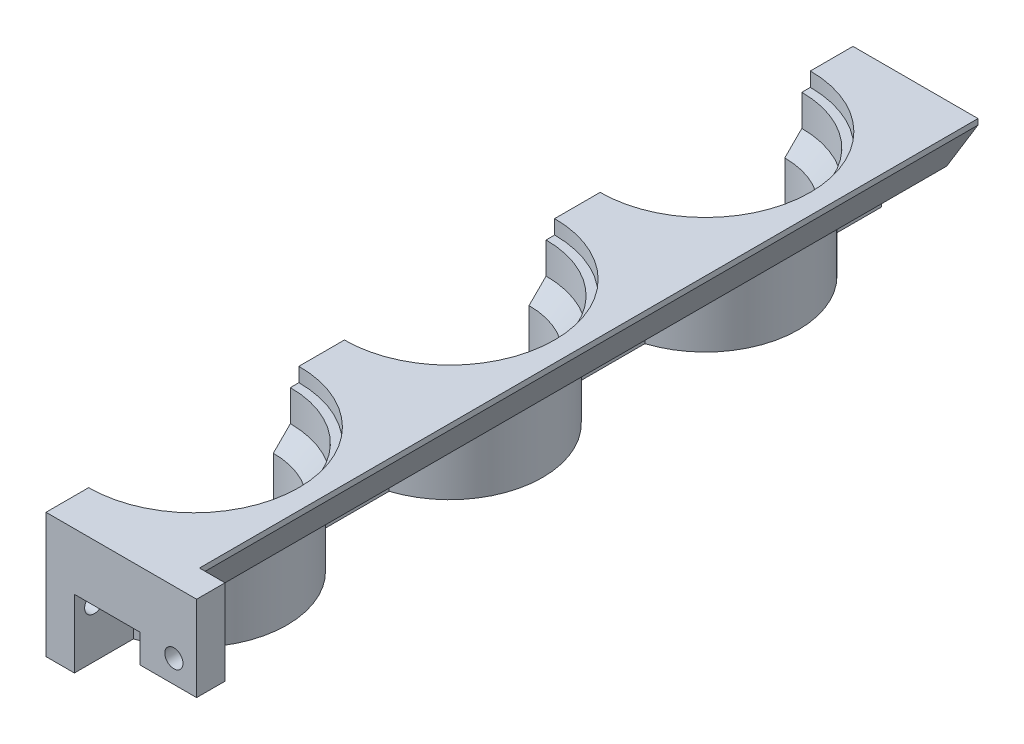
SolidWorks part; units mm, degrees
ref_plane "Płaszczyzna przednia" through (0, 0, 0) normal (0, 0, 1) x (1, 0, 0)
ref_plane "Płaszczyzna górna" through (0, 0, 0) normal (0, 1, 0) x (1, 0, 0)
ref_plane "Płaszczyzna prawa" through (0, 0, 0) normal (1, 0, 0) x (0, 0, -1)
sketch "Sketch1" plane through (0, 0, 0) normal (0, 1, 0) x (1, 0, 0)
  line L0 (0, 65.8555) -> (0, -65.8555) construction
  line L1 (0, -11.4) -> (0, -26)
  line L2 (0, -26) -> (22, -26)
  line L3 (104.3478, 45) -> (-104.3478, 45) construction
  line L4 (22, -26) -> (22, 116)
  line L5 (0, 101.4) -> (0, 116)
  line L6 (0, 116) -> (22, 116)
  line L7 (0, 11.4) -> (0, 33.6)
  line L8 (0, 56.4) -> (0, 78.6)
  arc A6 (0, -11.4) -> (0, 11.4) centre (0, 0) ccw
  arc A7 (0, 33.6) -> (0, 56.4) centre (0, 45) ccw
  arc A8 (0, 78.6) -> (0, 101.4) centre (0, 90) ccw
  point P7 (0, 0)
  point P20 (0, 45)
  point P23 (22, 45)
  dimension "D1" = 71
  dimension "D2" = 11.4
  dimension "D3" = 45
  dimension "D6" = 3
  dimension "D5" = 22
extrude "Boss-Extrude1" add sketch "Sketch1" against normal blind 10
sketch "Sketch3" plane through (0, -10, 0) normal (0, -1, 0) x (1, 0, 0)
  line L23 (0, -116) -> (0, -101.4)
  line L24 (0, -78.6) -> (0, -56.4)
  line L25 (0, -33.6) -> (0, -11.4)
  line L26 (0, 11.4) -> (0, 26)
  line L27 (5, -116) -> (5, -105.6192)
  line L28 (5, -74.3808) -> (5, -60.6192)
  line L29 (5, -29.3808) -> (5, -15.6192)
  line L30 (5, 15.6192) -> (5, 26)
  line L31 (5, -116) -> (5, -105.6192)
  line L32 (5, -74.3808) -> (5, -60.6192)
  line L33 (5, -29.3808) -> (5, -15.6192)
  line L34 (5, 15.6192) -> (5, 26)
  line L35 (0, 26) -> (5, 26)
  line L36 (0, -116) -> (5, -116)
  arc A15 (0, -101.4) -> (0, -78.6) centre (0, -90) ccw
  arc A16 (0, -56.4) -> (0, -33.6) centre (0, -45) ccw
  arc A17 (0, -11.4) -> (0, 11.4) centre (0, 0) ccw
  arc A18 (5, -105.6192) -> (5, -74.3808) centre (0, -90) ccw
  arc A19 (5, -60.6192) -> (5, -29.3808) centre (0, -45) ccw
  arc A20 (5, -15.6192) -> (5, 15.6192) centre (0, 0) ccw
  arc A21 (5, -105.6192) -> (5, -74.3808) centre (0, -90) ccw
  arc A22 (5, -60.6192) -> (5, -29.3808) centre (0, -45) ccw
  arc A23 (5, -15.6192) -> (5, 15.6192) centre (0, 0) ccw
  dimension "D1" = 5
extrude "Boss-Extrude2" add sketch "Sketch3" along normal blind 12
chamfer "Chamfer2" distance 5.5 distance2 9 1 edges at (22, -10, -45)
ref_plane "Plane1" through (0, 0, -80.5) normal (0, 0, 1) x (1, 0, 0)
sketch "Sketch6" plane through (0, 0, 0) normal (-1, 0, 0) x (0, 0, 1)
  line L0 (-101.4, 0) -> (-78.6, 0) construction
  line L1 (-76, -11) -> (-76, -26)
  line L2 (-90, 3.7296) -> (-90, -25.2968) construction
  line L3 (-90, 0) -> (-73, 0)
  line L4 (-73, 0) -> (-73, -8)
  line L5 (-90, -11) -> (-76, -11)
  line L6 (-73, -8) -> (-76, -11)
  line L7 (-90, -26) -> (-76, -26)
  line L8 (-90, 0) -> (-90, -26)
  line L10 (-90, 0) -> (-71.5, 0)
  line L11 (-90, 0) -> (-90, -2.5)
  line L12 (-90, -2.5) -> (-71.5, -2.5)
  line L13 (-71.5, 0) -> (-71.5, -2.5)
  point P3 (-90, 0)
  point P16 (-90, 0)
  dimension "D1" = 17
  dimension "D2" = 8
  dimension "D3" = 14
  dimension "D4" = 3
  dimension "D5" = 15
  dimension "D6" = 18.5
  dimension "D7" = 2.5
revolve "Cut-Revolve6" cut sketch "Sketch6" angle 360 about L8
pattern_linear "LPattern3" count 3 spacing 45 along (0, 0, 1) of "Cut-Revolve6"
sketch "Sketch7" plane through (5, 0, 0) normal (1, 0, 0) x (0, 0, -1)
  line L0 (74.3808, -10) -> (60.6192, -16) construction
  line L1 (60.6192, -22) -> (60.6192, -10) construction
  circle A0 centre (67.5, -13) radius 1.7
  point P3 (67.5, -13)
  dimension "D1" = 3.4
extrude "Cut-Extrude1" cut sketch "Sketch7" against normal blind 10
pattern_linear "LPattern4" count 3 spacing 45 along (0, 0, 1) of "Cut-Extrude1"
pattern_linear "LPattern5" count 2 spacing 45 along (0, 0, -1) of "Cut-Extrude1"
sketch "Sketch8" plane through (0, 0, 26) normal (0, 0, 1) x (1, 0, 0)
  line L1 (0, 0) -> (22, 0) construction
  line L2 (16.5, 0) -> (26.5, 0)
  line L3 (16.5, 0) -> (16.5, -15)
  line L4 (16.5, -15) -> (26.5, -15)
  line L5 (26.5, 0) -> (26.5, -15)
  circle A0 centre (22.5, -11) radius 1.6
  point P10 (0, 0)
  point P11 (0, 0)
  point P14 (23.3889, -7.5717)
  dimension "D1" = 3.2
  dimension "D2" = 10
  dimension "D3" = 15
  dimension "D4" = 6
  dimension "D5" = 11
extrude "Boss-Extrude3" add sketch "Sketch8" against normal blind 5
